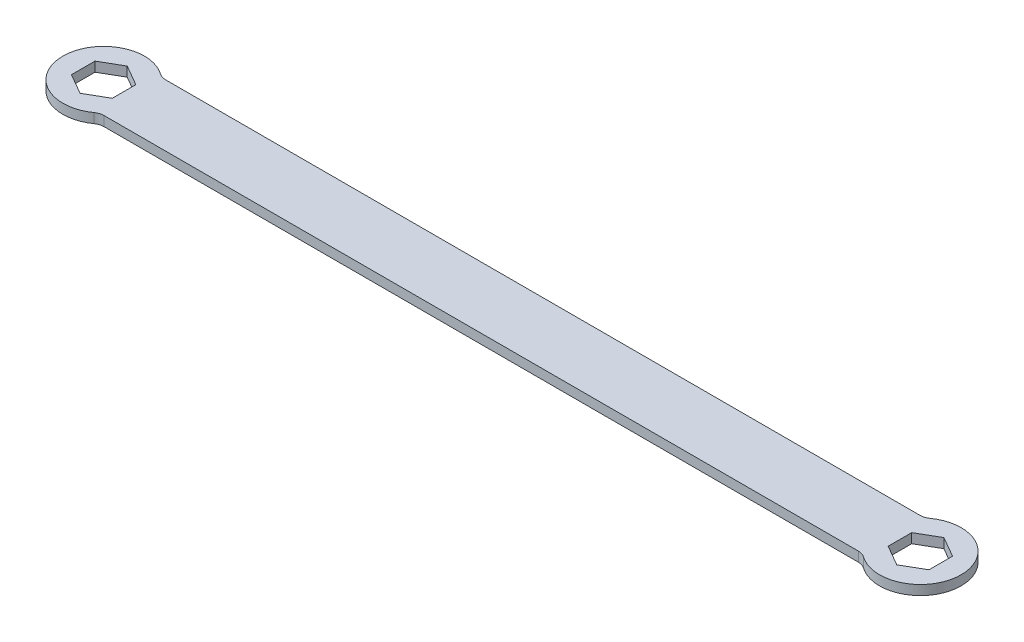
SolidWorks part; units mm, degrees
other "Defeature"
material "Plain Carbon Steel"
ref_plane "Front Plane" through (0, 0, 0) normal (0, 0, 1) x (1, 0, 0)
ref_plane "Top Plane" through (0, 0, 0) normal (0, 1, 0) x (1, 0, 0)
ref_plane "Right Plane" through (0, 0, 0) normal (1, 0, 0) x (0, 0, -1)
sketch "Sketch1" plane through (0, 0, 0) normal (0, 1, 0) x (1, 0, 0)
  line L1 (-59.35, -4.8) -> (59.35, -4.8)
  line L2 (-59.35, -4.8) -> (-59.35, 4.8)
  line L3 (-59.35, 4.8) -> (59.35, 4.8)
  line L4 (59.35, -4.8) -> (59.35, 4.8)
  line L5 (-59.35, -4.8) -> (59.35, 4.8) construction
  line L6 (-59.35, 4.8) -> (59.35, -4.8) construction
  line L7 (-60.3322, 1.8331) -> (-63.5072, 3.6662)
  line L8 (-63.5072, 3.6662) -> (-66.6822, 1.8331)
  line L9 (-66.6822, 1.8331) -> (-66.6822, -1.8331)
  line L10 (-66.6822, -1.8331) -> (-63.5072, -3.6662)
  line L11 (-63.5072, -3.6662) -> (-60.3322, -1.8331)
  line L12 (-60.3322, -1.8331) -> (-60.3322, 1.8331)
  line L13 (63.5072, -3.6662) -> (66.6822, -1.8331)
  line L14 (66.6822, -1.8331) -> (66.6822, 1.8331)
  line L15 (66.6822, 1.8331) -> (63.5072, 3.6662)
  line L16 (63.5072, 3.6662) -> (60.3322, 1.8331)
  line L17 (60.3322, 1.8331) -> (60.3322, -1.8331)
  line L18 (60.3322, -1.8331) -> (63.5072, -3.6662)
  arc A0 (59.35, 4.8) -> (59.35, -4.8) centre (63.5072, 0) cw
  arc A1 (-59.35, 4.8) -> (-59.35, -4.8) centre (-63.5072, 0) ccw
  circle A2 centre (-63.5072, 0) radius 3.175 construction
  circle A3 centre (63.5072, 0) radius 3.175 construction
  point P0 (0, 0)
  dimension "D4" = 6.35
  dimension "D1" = 6.35
  dimension "D2" = 118.7
  dimension "D3" = 9.6
extrude "Boss-Extrude1" add sketch "Sketch1" along normal mid plane 1.5 contours A0 L4 L18 L17 L16 L15 L14 L13 | L1 L4 L3 L2 | L2 A1 L12 L11 L10 L9 L8 L7
fillet "Fillet1" radius 2 4 edges at (-59.35, 0, 4.8) (-59.35, 0, -4.8) (59.35, 0, -4.8) (59.35, 0, 4.8)
